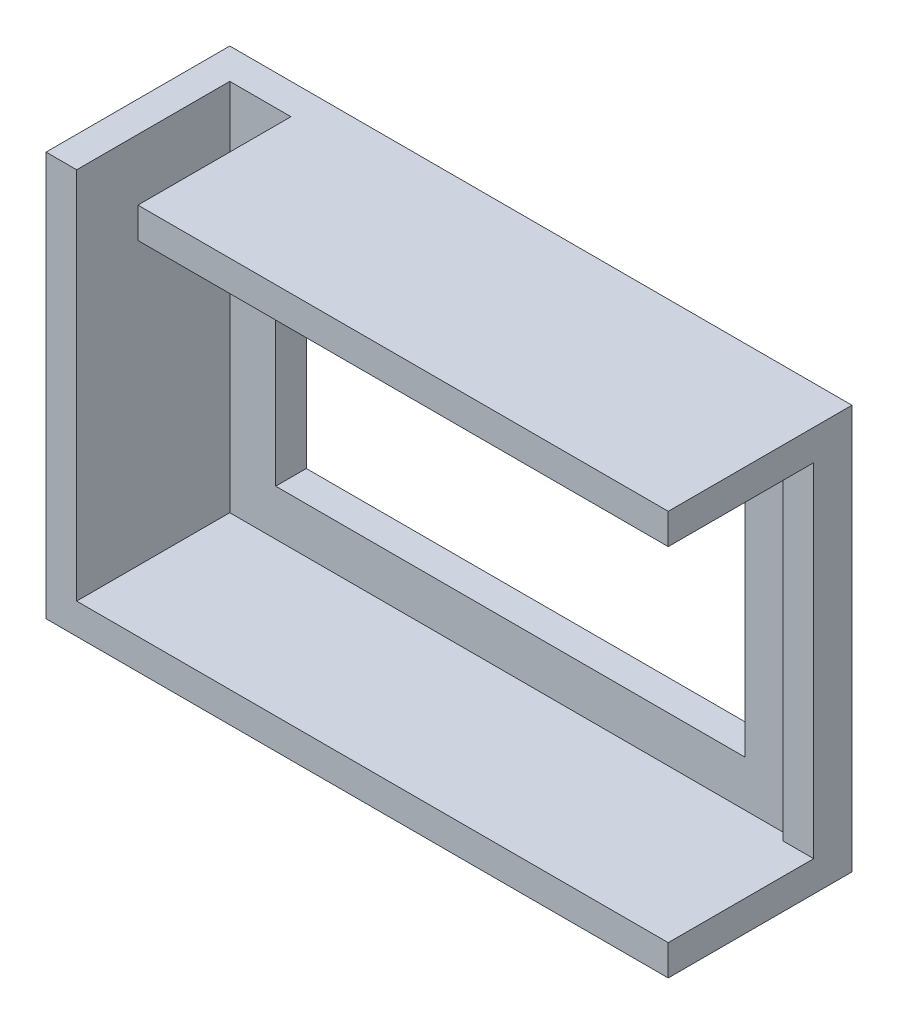
SolidWorks part; units mm, degrees
ref_plane "Plan de face" through (0, 0, 0) normal (0, 0, 1) x (1, 0, 0)
ref_plane "Plan de dessus" through (0, 0, 0) normal (0, 1, 0) x (1, 0, 0)
ref_plane "Plan de droite" through (0, 0, 0) normal (1, 0, 0) x (0, 0, -1)
sketch "Esquisse1" plane through (0, 0, 0) normal (0, 0, 1) x (1, 0, 0)
  line L1 (0, 0) -> (20.32, 0)
  line L2 (0, 0) -> (0, 13.2)
  line L3 (0, 13.2) -> (20.32, 13.2)
  line L4 (20.32, 0) -> (20.32, 13.2)
  dimension "D1" = 20.32
  dimension "D2" = 13.2
extrude "Boss.-Extru.1" add sketch "Esquisse1" along normal blind 6
sketch "Esquisse2" plane through (0, 0, 6) normal (0, 0, 1) x (1, 0, 0)
  line L0 (0, 13.2) -> (0, 0) construction
  line L1 (1, 1) -> (19.32, 1)
  line L2 (1, 1) -> (1, 12.2)
  line L3 (1, 12.2) -> (19.32, 12.2)
  line L4 (19.32, 1) -> (19.32, 12.2)
  line L5 (0, 0) -> (20.32, 0) construction
  line L6 (20.32, 13.2) -> (0, 13.2) construction
  line L7 (20.32, 0) -> (20.32, 13.2) construction
  dimension "D1" = 1
  dimension "D2" = 1
  dimension "D3" = 1
  dimension "D4" = 1
extrude "Enlèv. mat.-Extru.1" cut sketch "Esquisse2" against normal blind 5
sketch "Esquisse3" plane through (0, 0, 6) normal (0, 0, 1) x (1, 0, 0)
  line L0 (1, 12.2) -> (1, 1) construction
  line L1 (1, 12.2) -> (3, 12.2)
  line L2 (1, 12.2) -> (1, 13.2)
  line L3 (1, 13.2) -> (3, 13.2)
  line L4 (3, 12.2) -> (3, 13.2)
  line L5 (19.32, 12.2) -> (1, 12.2) construction
  line L6 (20.32, 13.2) -> (0, 13.2) construction
  dimension "D1" = 0
  dimension "D2" = 0
  dimension "D3" = 0
  dimension "D4" = 2
extrude "Enlèv. mat.-Extru.2" cut sketch "Esquisse3" against normal blind 5
sketch "Esquisse4" plane through (0, 0, 1) normal (0, 0, 1) x (1, 0, 0)
  line L0 (1, 13.2) -> (1, 1) construction
  line L1 (2.5, 10.7) -> (17.82, 10.7)
  line L2 (2.5, 10.7) -> (2.5, 2.5)
  line L3 (2.5, 2.5) -> (17.82, 2.5)
  line L4 (17.82, 10.7) -> (17.82, 2.5)
  line L5 (1, 1) -> (19.32, 1) construction
  line L6 (19.32, 1) -> (19.32, 12.2) construction
  line L7 (19.32, 12.2) -> (3, 12.2) construction
  dimension "D1" = 1.5
  dimension "D2" = 1.5
  dimension "D3" = 1.5
  dimension "D4" = 1.5
extrude "Enlèv. mat.-Extru.3" cut sketch "Esquisse4" against normal through all
sketch "Esquisse6" plane through (0, 0, 6) normal (0, 0, 1) x (1, 0, 0)
  line L0 (19.32, 12.2) -> (3, 12.2) construction
  line L1 (19.32, 12.2) -> (20.32, 12.2)
  line L2 (19.32, 12.2) -> (19.32, 1)
  line L3 (19.32, 1) -> (20.32, 1)
  line L4 (20.32, 12.2) -> (20.32, 1)
  line L5 (1, 1) -> (19.32, 1) construction
  line L6 (19.32, 1) -> (19.32, 12.2) construction
  line L7 (20.32, 0) -> (20.32, 13.2) construction
  dimension "D1" = 0
  dimension "D2" = 0
  dimension "D3" = 0
  dimension "D4" = 0
extrude "Enlèv. mat.-Extru.4" cut sketch "Esquisse6" against normal blind 4.75
